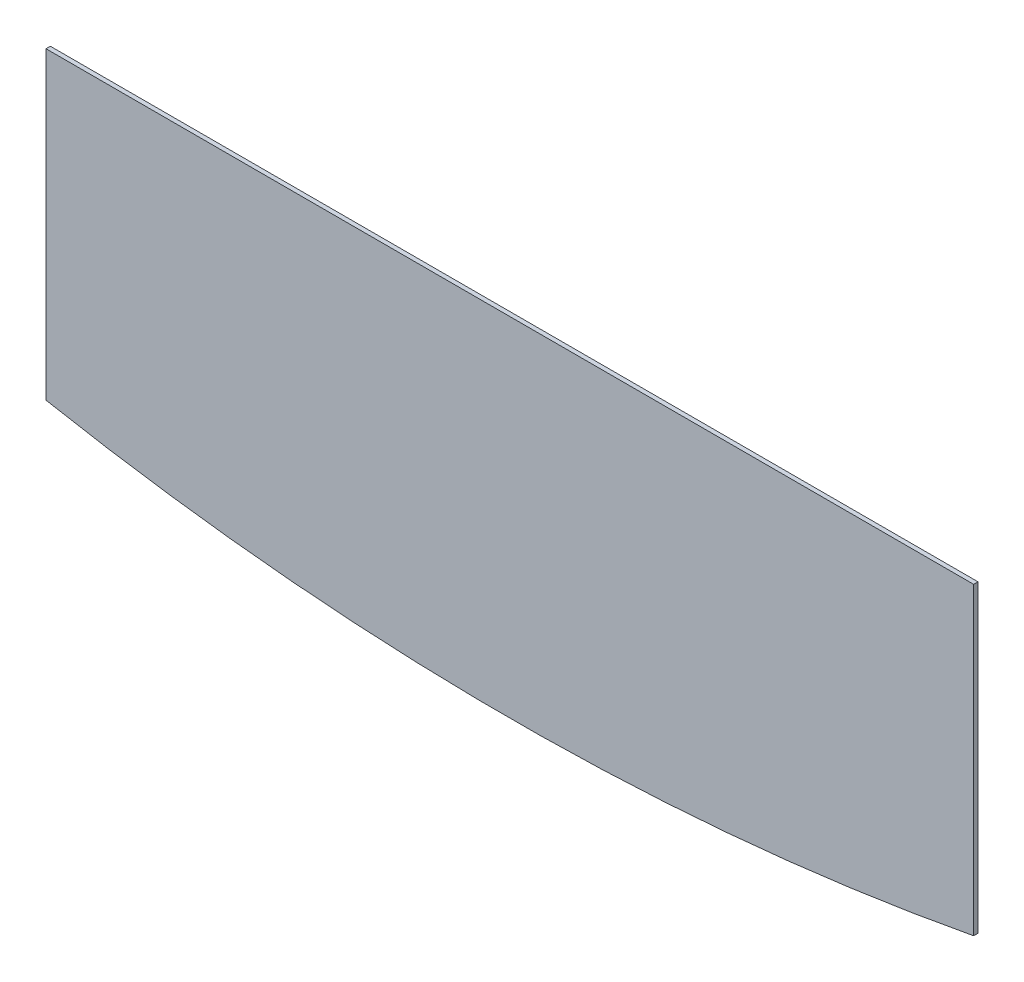
SolidWorks part; units mm, degrees
ref_plane "Plan de face" through (0, 0, 0) normal (0, 0, 1) x (1, 0, 0)
ref_plane "Plan de dessus" through (0, 0, 0) normal (0, 1, 0) x (1, 0, 0)
ref_plane "Plan de droite" through (0, 0, 0) normal (1, 0, 0) x (0, 0, -1)
sketch "Esquisse1" plane through (0, 0, 0) normal (0, 0, 1) x (1, 0, 0)
  line L1 (0, 0) -> (320, 0)
  line L2 (0, 0) -> (0, 120)
  line L3 (0, 120) -> (320, 120)
  line L4 (320, 0) -> (320, 120)
  dimension "D1" = 320
  dimension "D2" = 120
extrude "Boss.-Extru.1" add sketch "Esquisse1" along normal blind 1.5
sketch "Esquisse2" plane through (0, 0, 1.5) normal (0, 0, 1) x (1, 0, 0)
  line L0 (0, 120) -> (0, 0) construction
  line L1 (320, 0) -> (320, 120) construction
  line L2 (0, 0) -> (320, 0) construction
  line L3 (320, 15) -> (0, 15) construction
  arc A0 (0, 15) -> (320, 15) centre (160, 860.8333) ccw
  dimension "D1" = 15
extrude "Enlèv. mat.-Extru.1" cut sketch "Esquisse2" against normal blind 1.5 and the other way through all flip side to cut
